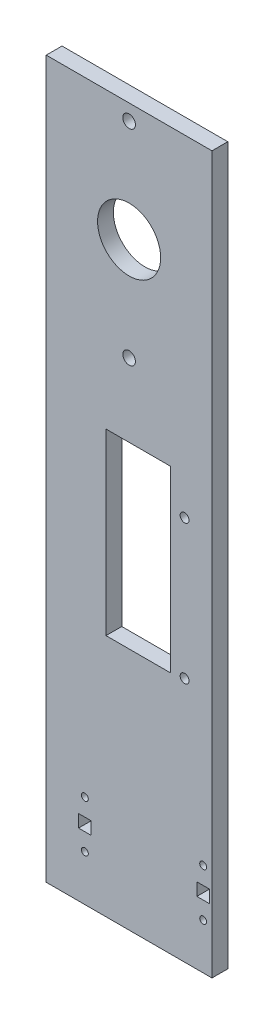
SolidWorks part; units mm, degrees
ref_plane "Front Plane" through (0, 0, 0) normal (0, 0, 1) x (1, 0, 0)
ref_plane "Top Plane" through (0, 0, 0) normal (0, 1, 0) x (1, 0, 0)
ref_plane "Right Plane" through (0, 0, 0) normal (1, 0, 0) x (0, 0, -1)
sketch "Sketch1" plane through (0, 0, 0) normal (0, 0, 1) x (1, 0, 0)
  line B0 (66.7, 0) -> (0, 0)
  line B1 (0, 0) -> (0, -288.29)
  line B2 (0, -288.29) -> (66.7, -288.29)
  line B3 (66.7, -288.29) -> (66.7, 0)
  line B4 (60.62, -262.89) -> (65.7, -262.89)
  line B5 (65.7, -257.81) -> (65.7, -262.89)
  line B6 (60.62, -257.81) -> (60.62, -262.89)
  line B7 (60.62, -257.81) -> (65.7, -257.81)
  line B8 (13, -262.89) -> (13, -257.81)
  line B9 (13, -257.81) -> (18.08, -257.81)
  line B10 (18.08, -262.89) -> (18.08, -257.81)
  line B11 (13, -262.89) -> (18.08, -262.89)
  line B12 (24.05, -118.29) -> (24.05, -190.29)
  line B13 (24.05, -190.29) -> (50.05, -190.29)
  line B14 (50.05, -190.29) -> (50.05, -118.29)
  line B15 (50.05, -118.29) -> (24.05, -118.29)
  circle B16 centre (63.16, -269.875) radius 1.3891
  circle B17 centre (63.16, -250.825) radius 1.3891
  circle B18 centre (15.54, -250.825) radius 1.3891
  circle B19 centre (15.54, -269.875) radius 1.3891
  circle B20 centre (55.675, -133.39) radius 1.7859
  circle B21 centre (55.675, -189.39) radius 1.7859
  circle B22 centre (33.35, -88.85) radius 2.54
  circle B23 centre (33.35, -47.6) radius 12.7
  circle B24 centre (33.35, -6.35) radius 2.54
sketch_block_instance "Base-1"
sketch_block "Base"
extrude "Boss-Extrude1" add sketch "Sketch1" along normal blind 6.35
